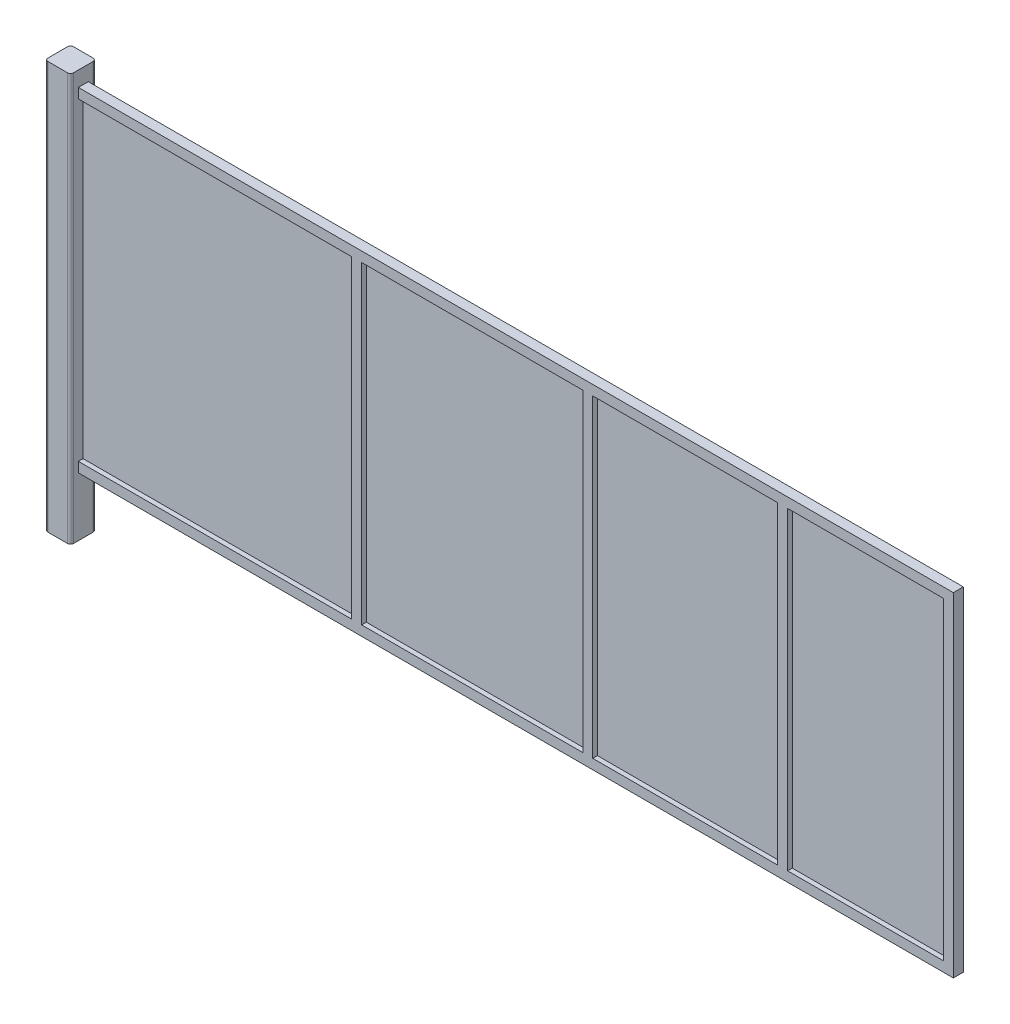
SolidWorks part; units mm, degrees
ref_plane "Alzado" through (0, 0, 0) normal (0, 0, 1) x (1, 0, 0)
ref_plane "Planta" through (0, 0, 0) normal (0, 1, 0) x (1, 0, 0)
ref_plane "Vista lateral" through (0, 0, 0) normal (1, 0, 0) x (0, 0, -1)
sketch "Croquis1" plane through (0, 0, 0) normal (0, 1, 0) x (1, 0, 0)
  line L1 (-34.389, 45) -> (34.389, 45)
  line L2 (-45, 34.389) -> (-45, -34.389)
  line L3 (-34.389, -45) -> (34.389, -45)
  line L4 (45, 34.389) -> (45, -34.389)
  line L5 (-45, 45) -> (45, -45) construction
  line L6 (-45, -45) -> (45, 45) construction
  arc A0 (34.389, 45) -> (45, 34.389) centre (34.389, 34.389) cw
  arc A1 (34.389, -45) -> (45, -34.389) centre (34.389, -34.389) ccw
  arc A2 (-45, -34.389) -> (-34.389, -45) centre (-34.389, -34.389) ccw
  arc A3 (-34.389, 45) -> (-45, 34.389) centre (-34.389, 34.389) ccw
  point P0 (0, 0)
  dimension "D3" = 10.611
  dimension "D1" = 90
  dimension "D2" = 90
extrude "Saliente-Extruir1" add sketch "Croquis1" along normal blind 1435
ref_plane "Plano1" through (0, 0, 0) normal (0, 0, 1) x (1, 0, 0)
sketch "Croquis2" plane through (0, 0, 0) normal (0, 0, 1) x (1, 0, 0)
  line L0 (45, 1435) -> (45, 1381.9129) construction
  line L1 (45, 1435) -> (45, 0) construction
  line L2 (45, 1381.9129) -> (3125, 1381.9129)
  line L3 (3125, 1381.9129) -> (3125, 207.0765)
  line L4 (3125, 207.0765) -> (45, 207.0765)
  line L5 (45, 207.0765) -> (45, 1381.9129) construction
  line L6 (45, 1346.9129) -> (1007.2537, 1346.9129)
  line L7 (3090, 1346.9129) -> (3090, 242.0765)
  line L8 (3090, 242.0765) -> (2541.6276, 242.0765)
  line L9 (1042.2537, 1346.9129) -> (1042.2537, 242.0765)
  line L10 (1855.7438, 1346.9129) -> (1855.7438, 242.0765)
  line L11 (2541.6276, 1346.9129) -> (2541.6276, 242.0765)
  line L12 (1007.2537, 1346.9129) -> (1007.2537, 242.0765)
  line L13 (1820.7438, 1346.9129) -> (1820.7438, 242.0765)
  line L14 (2506.6276, 1346.9129) -> (2506.6276, 242.0765)
  line L15 (1042.2537, 1346.9129) -> (1820.7438, 1346.9129)
  line L16 (45, 1346.9129) -> (3090, 1346.9129) construction
  line L17 (1855.7438, 1346.9129) -> (2506.6276, 1346.9129)
  line L18 (2541.6276, 1346.9129) -> (3090, 1346.9129)
  line L19 (2506.6276, 242.0765) -> (1855.7438, 242.0765)
  line L20 (3090, 242.0765) -> (45, 242.0765) construction
  line L21 (1820.7438, 242.0765) -> (1042.2537, 242.0765)
  line L22 (1007.2537, 242.0765) -> (45, 242.0765)
  line L23 (45, 1381.9129) -> (45, 1346.9129)
  line L24 (45, 242.0765) -> (45, 207.0765)
  dimension "D1" = 3080
  dimension "D2" = 35
  dimension "D3" = 35
extrude "Saliente-Extruir2" add sketch "Croquis2" along normal blind 17.5 and the other way blind 17.5
sketch "Croquis3" plane through (0, 0, 0) normal (0, 0, 1) x (1, 0, 0)
  line L0 (45, 1346.9129) -> (1007.2537, 1346.9129)
  line L1 (1007.2537, 1346.9129) -> (1007.2537, 242.0765)
  line L2 (1007.2537, 242.0765) -> (45, 242.0765) construction
  line L3 (1007.2537, 1346.9129) -> (1007.2537, 242.0765) construction
  line L4 (1007.2537, 242.0765) -> (45, 242.0765)
  line L5 (45, 1346.9129) -> (45, 242.0765)
  line L6 (1042.2537, 1346.9129) -> (1042.2537, 242.0765)
  line L7 (1042.2537, 242.0765) -> (1820.7438, 242.0765)
  line L8 (1820.7438, 242.0765) -> (1820.7438, 1346.9129)
  line L9 (1820.7438, 1346.9129) -> (1042.2537, 1346.9129)
  line L10 (1855.7438, 1346.9129) -> (2506.6276, 1346.9129)
  line L11 (2506.6276, 1346.9129) -> (2506.6276, 242.0765)
  line L12 (2506.6276, 242.0765) -> (1855.7438, 242.0765)
  line L13 (1855.7438, 242.0765) -> (1855.7438, 1346.9129)
  line L14 (3090, 1346.9129) -> (2541.6276, 1346.9129)
  line L15 (2541.6276, 1346.9129) -> (2541.6276, 242.0765)
  line L16 (2541.6276, 242.0765) -> (3090, 242.0765)
  line L17 (3090, 242.0765) -> (3090, 1346.9129)
extrude "Saliente-Extruir3" add sketch "Croquis3" along normal blind 1
